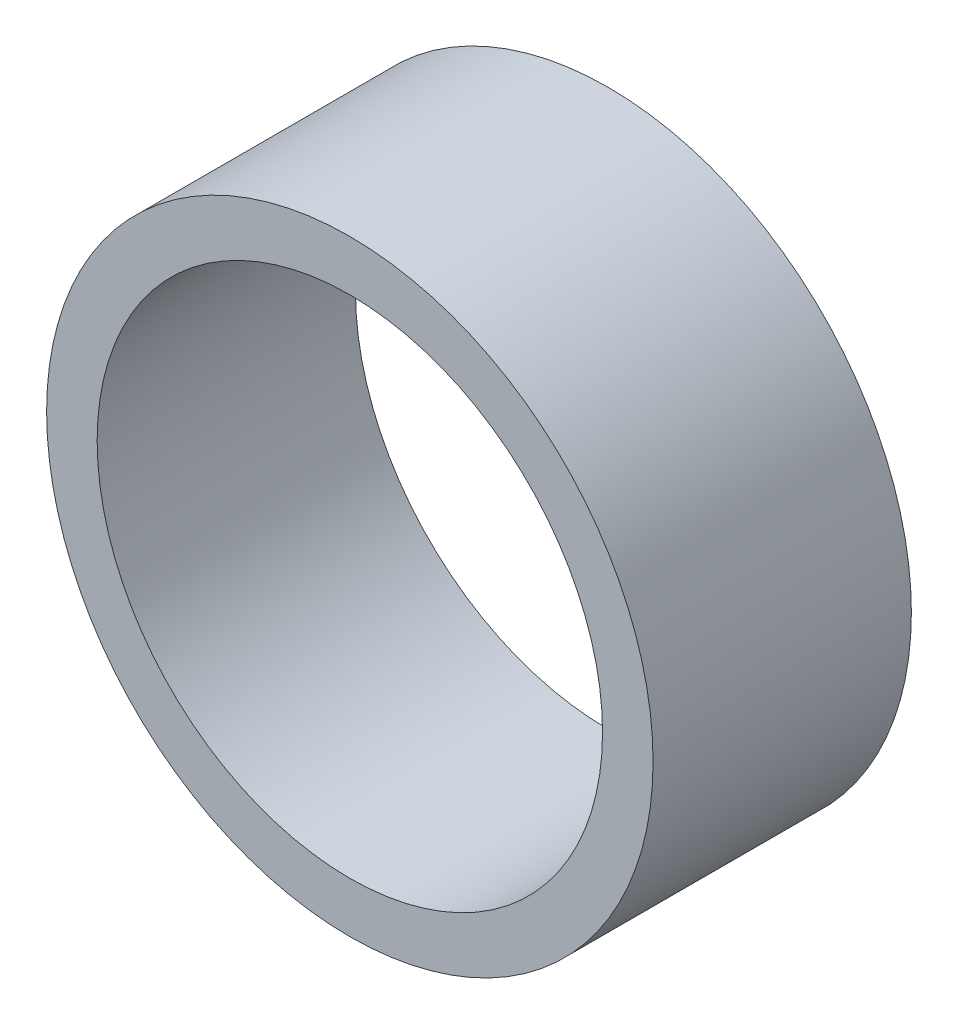
SolidWorks part; units mm, degrees
material "AISI 4340 Aço, normalizado"
ref_plane "Plano frontal" through (0, 0, 0) normal (0, 0, 1) x (1, 0, 0)
ref_plane "Plano superior" through (0, 0, 0) normal (0, 1, 0) x (1, 0, 0)
ref_plane "Plano direito" through (0, 0, 0) normal (1, 0, 0) x (0, 0, -1)
sketch "Esboço1" plane through (0, 0, 0) normal (0, 0, 1) x (1, 0, 0)
  circle A0 centre (0, 0) radius 22.5
  circle A1 centre (0, 0) radius 27
  dimension "D1" = 54
  dimension "D2" = 45
extrude "Ressalto-extrusão1" add sketch "Esboço1" along normal blind 23
equation "\"escala\"= 1                        'projeto - escala geral"
equation "\"escala_disco-arma\"= 3                                                                  'disco arma - escala geometria disco arma"
equation "\"arma_eixo-furo_folga\"= 4                                                              'disco arma - folga entre furo arma e eixo"
equation "\"arma_rebaixo-camisa_raio\"= 12                                                         'disco arma - raio do rebaixo da camisa da arma "
equation "\"arma_rebaixo-camisa_b\"= \"rolamento_b-esp\" + (\"arma-espessura\"-\"rolamento_b-esp\")/2     'disco arma - profundidade rebaixo camisa"
equation "\"arma-espessura\"= 50                                                                    'disco arma - espessura disco arma"
equation "\"rolamento_D-ext\"= 85               'rolamento arma - diametro externo"
equation "\"rolamento_D1-ext\"= 75             'rolamento arma - ressalto diam externo"
equation "\"rolamento_d-int\"= 45               'rolamento arma - diametro interno"
equation "\"rolamento_d2-int\"= 54             'rolamento arma - ressalto diam interno"
equation "\"rolamento_b-esp\"= 23               'rolamento arma - espessura"
equation "\"eixo-arm_diam\"= \"rolamento_d-int\"                                                                'eixo arma - diametro"
equation "\"eixo-arm_folga_mancal-arma\"= 10"
equation "\"eixo-arm_allowable-movement\"= 1"
equation "\"eixo-arm_comp-entre-mancais\"= 2*\"eixo-arm_folga_mancal-arma\" + 2*\"arma-espessura\" + \"polia_espessura\"    'eixo arma - comprimento entre mancais"
equation "\"eixo-arm_comp-espacador\"= \"eixo-arm_folga_mancal-arma\" + \"arma-espessura\"-\"arma_rebaixo-camisa_b\" - \"eixo-arm_allowable-movement\"/2"
equation "\"eixo-arm_prof-furo-fix\"= 30"
equation "\"mancal-arm_rebaixo-eixo_profundidade\"= 20"
equation "\"mancal-arm_rebaixo-eixo_diametro\"= 2 * \"eixo-arm_diam\" - \"rolamento_d2-int\""
equation "\"camisa_largura\"=115                                                        'camisa arma - tamanho do lado"
equation "\"camisa_raio\"= 16                                                           'camisa arma - raio canto interno"
equation "\"camisa_raio-alivio\"= 6                                                    'camisa arma - raio de alivio de tensoes no encaixe da arma"
equation "\"camisa_rebaixo_rolamento\"= 1 * \"rolamento_b-esp\""
equation "\"camisa_comprimento-centro\"= 2*(\"arma_rebaixo-camisa_b\")+\"polia_espessura\" "
equation "\"camisa_furos_dist\"= 83"
equation "\"camisa_furos_prof\"= 30"
equation "\"polia_espessura\"= 40  "
equation "\"polia_diam_eff\"= 142"
equation "\"D1@Esboço1\"=\"rolamento_d2-int\""
equation "\"D2@Esboço1\"=\"rolamento_d-int\""
equation "\"D1@Ressalto-extrusão1\"=\"eixo-arm_comp-espacador\""
